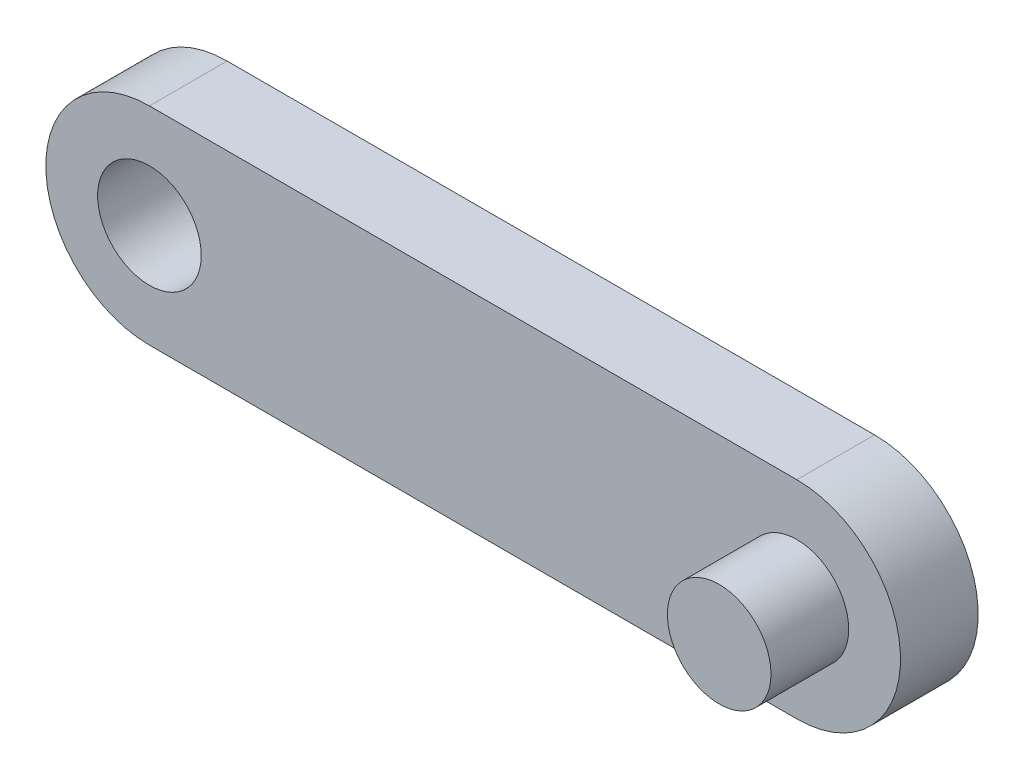
SolidWorks part; units mm, degrees
ref_plane "Front Plane" through (0, 0, 0) normal (0, 0, 1) x (1, 0, 0)
ref_plane "Top Plane" through (0, 0, 0) normal (0, 1, 0) x (1, 0, 0)
ref_plane "Right Plane" through (0, 0, 0) normal (1, 0, 0) x (0, 0, -1)
sketch "Sketch2" plane through (0, 0, 0) normal (0, 0, 1) x (1, 0, 0)
  line L4 (0, 0) -> (250, 0)
  line L6 (0, -80) -> (250, -80)
  arc A0 (0, 0) -> (0, -80) centre (0, -40) ccw
  arc A1 (250, -80) -> (250, 0) centre (250, -40) ccw
  circle A3 centre (0, -40) radius 20
  dimension "D3" = 40
  dimension "D4" = 80
  dimension "D1" = 250
extrude "Boss-Extrude1" add sketch "Sketch2" along normal blind 30
sketch "Sketch3" plane through (0, 0, 30) normal (0, 0, 1) x (1, 0, 0)
  point P0 (0, -40)
  point P1 (0, 0)
sketch "Sketch7" plane through (0, 0, 30) normal (0, 0, 1) x (1, 0, 0)
  circle A0 centre (250, -40) radius 20
  dimension "D1" = 40
  dimension "D2" = 40
extrude "Boss-Extrude2" add sketch "Sketch7" along normal blind 30
